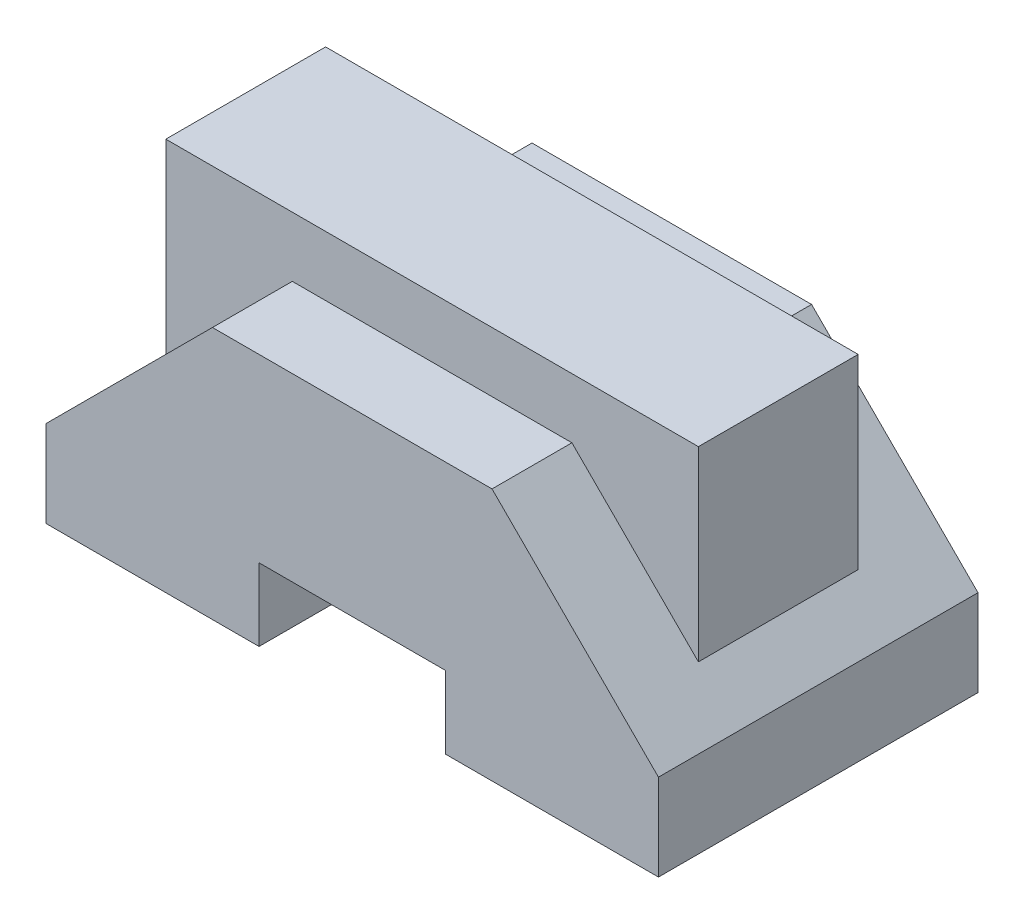
SolidWorks part; units mm, degrees
ref_plane "Front Plane" through (0, 0, 0) normal (0, 0, 1) x (1, 0, 0)
ref_plane "Top Plane" through (0, 0, 0) normal (0, 1, 0) x (1, 0, 0)
ref_plane "Right Plane" through (0, 0, 0) normal (1, 0, 0) x (0, 0, -1)
sketch "Sketch1" plane through (0, 0, 0) normal (0, 0, 1) x (1, 0, 0)
  line L0 (14, 0) -> (46, 0)
  line L1 (46, 0) -> (46, 13)
  line L2 (46, 13) -> (21, 38)
  line L3 (21, 38) -> (-21, 38)
  line L4 (0, 38) -> (0, 10.8912)
  line L5 (-14, 10.8912) -> (14, 10.8912)
  line L6 (14, 10.8912) -> (14, 0)
  line L7 (-14, 10.8912) -> (-14, 0)
  line L8 (-46, 13) -> (-21, 38)
  line L9 (-46, 0) -> (-46, 13)
  line L10 (-14, 0) -> (-46, 0)
  dimension "D1" = 13
  dimension "D2" = 14
  dimension "D3" = 46
  dimension "D4" = 21
  dimension "D5" = 38
extrude "Boss-Extrude1" add sketch "Sketch1" along normal mid plane 48 contours L10 L7 L5 L4 L3 L8 L9 | L5 L6 L0 L1 L2 L3 L4
sketch "Sketch2" plane through (0, 0, 0) normal (0, 1, 0) x (1, 0, 0)
  line L1 (-40, -12) -> (40, -12)
  line L2 (-40, -12) -> (-40, 12)
  line L3 (-40, 12) -> (40, 12)
  line L4 (40, -12) -> (40, 12)
  line L5 (-40, -12) -> (40, 12) construction
  line L6 (-40, 12) -> (40, -12) construction
  point P0 (0, 0)
  dimension "D1" = 24
  dimension "D2" = 80
extrude "Boss-Extrude2" add sketch "Sketch2" against normal blind 36 from offset 47
